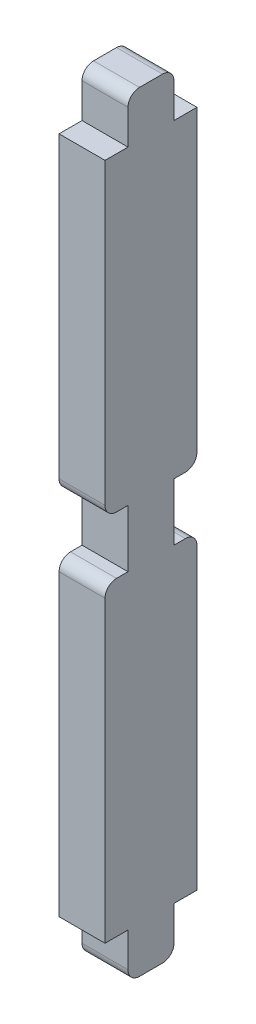
SolidWorks part; units mm, degrees
ref_plane "Front Plane" through (0, 0, 0) normal (1, 0, 0) x (0, 1, 0)
ref_plane "Top Plane" through (0, 0, 0) normal (0, 0, 1) x (0, 1, 0)
ref_plane "Right Plane" through (0, 0, 0) normal (0, 1, 0) x (-1, 0, 0)
sketch "Sketch1" plane through (0, 0, 0) normal (1, 0, 0) x (0, 1, 0)
  line L0 (-33.5, 2) -> (33.5, -2) construction
  line L1 (-33.5, -2) -> (33.5, -2) construction
  line L2 (-33.5, -2) -> (-33.5, 2) construction
  line L3 (-33.5, 2) -> (33.5, 2) construction
  line L4 (33.5, -2) -> (33.5, 2) construction
  line L5 (-33.5, 0) -> (-29.5, 0) construction
  line L6 (-29.5, -4) -> (-2.5, -4) construction
  line L7 (-29.5, -4) -> (-29.5, 4) construction
  line L8 (-29.5, 4) -> (-2.5, 4) construction
  line L9 (-2.5, -4) -> (-2.5, 4) construction
  line L10 (2.5, -4) -> (29.5, -4) construction
  line L11 (2.5, -4) -> (2.5, 4) construction
  line L12 (2.5, 4) -> (29.5, 4) construction
  line L13 (29.5, -4) -> (29.5, 4) construction
  line L14 (-29.5, 0) -> (-2.5, 0) construction
  line L15 (-2.5, 0) -> (2.5, 0) construction
  line L16 (2.5, 0) -> (29.5, 0) construction
  line L17 (29.5, 0) -> (33.5, 0) construction
  line L18 (-33.5, -2) -> (-33.5, 2)
  line L19 (-33.5, 2) -> (-29.5, 2)
  line L20 (-29.5, 2) -> (-29.5, 4)
  line L22 (29.5, 4) -> (29.5, 2)
  line L23 (29.5, 2) -> (33.5, 2)
  line L24 (33.5, 2) -> (33.5, -2)
  line L25 (33.5, -2) -> (29.5, -2)
  line L26 (29.5, -2) -> (29.5, -4)
  line L28 (-29.5, -4) -> (-29.5, -2)
  line L29 (-29.5, -2) -> (-33.5, -2)
  line L30 (-29.5, 4) -> (-2.5, 4)
  line L31 (-2.5, 4) -> (-2.5, 2)
  line L32 (-2.5, 2) -> (2.5, 2)
  line L33 (2.5, 2) -> (2.5, 4)
  line L34 (2.5, 4) -> (29.5, 4)
  line L35 (29.5, -4) -> (2.5, -4)
  line L36 (2.5, -4) -> (2.5, -2)
  line L37 (2.5, -2) -> (-2.5, -2)
  line L38 (-2.5, -2) -> (-2.5, -4)
  line L39 (-2.5, -4) -> (-29.5, -4)
  point P25 (-2.5, -2)
  point P28 (2.5, -2)
  point P29 (2.5, 2)
  point P30 (-2.5, 2)
  dimension "D1" = 67
  dimension "D2" = 4
  dimension "D3" = 4
  dimension "D4" = 4
  dimension "D5" = 8
  dimension "D6" = 5
extrude "Boss-Extrude1" add sketch "Sketch1" along normal blind 4
fillet "Fillet1" radius 1 4 edges at (2, 2.5, -4) (2, -2.5, -4) (2, 2.5, 4) (2, -2.5, 4)
fillet "Fillet2" radius 1 4 edges at (2, -33.5, 2) (2, -33.5, -2) (2, 33.5, -2) (2, 33.5, 2)
